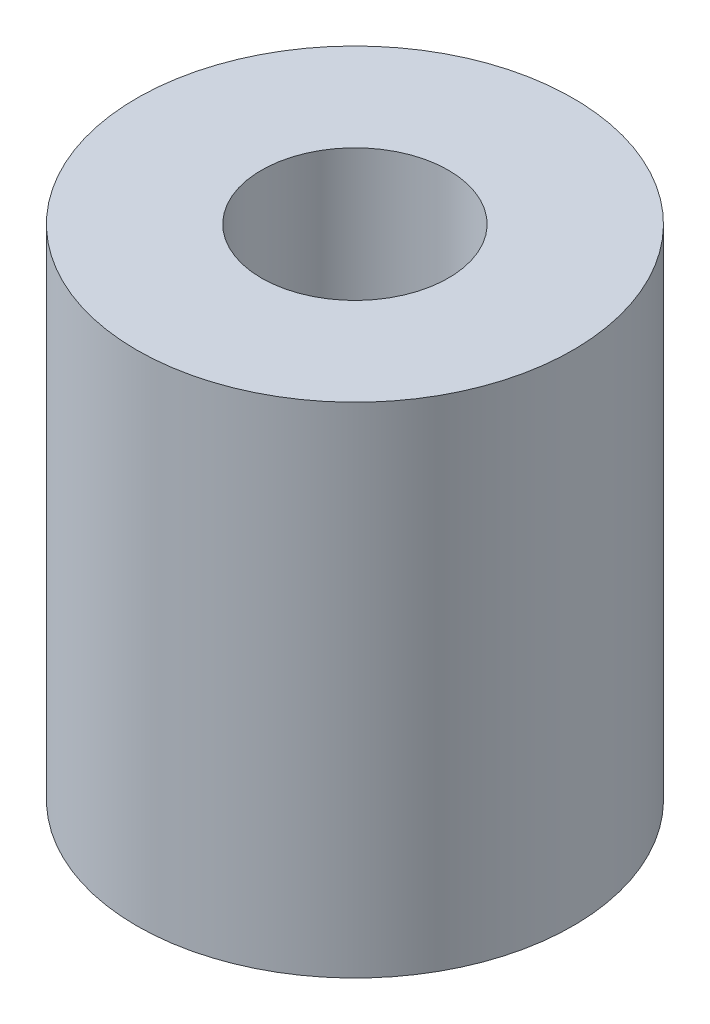
SolidWorks part; units mm, degrees
ref_plane "Alzado" through (0, 0, 0) normal (0, 0, 1) x (1, 0, 0)
ref_plane "Planta" through (0, 0, 0) normal (0, 1, 0) x (1, 0, 0)
ref_plane "Vista lateral" through (0, 0, 0) normal (1, 0, 0) x (0, 0, -1)
sketch "Croquis base" plane through (0, 0, 0) normal (0, 1, 0) x (1, 0, 0)
  circle A0 centre (0, 0) radius 3.5
  dimension "D1" = 7
extrude "Saliente-Extruir1" add sketch "Croquis base" along normal blind 8
sketch "Croquis barreno" plane through (0, 8, 0) normal (0, 1, 0) x (1, 0, 0)
  circle A0 centre (0, 0) radius 1.5
  dimension "D1" = 3
extrude "Cortar-Extruir1" cut sketch "Croquis barreno" against normal blind 8
